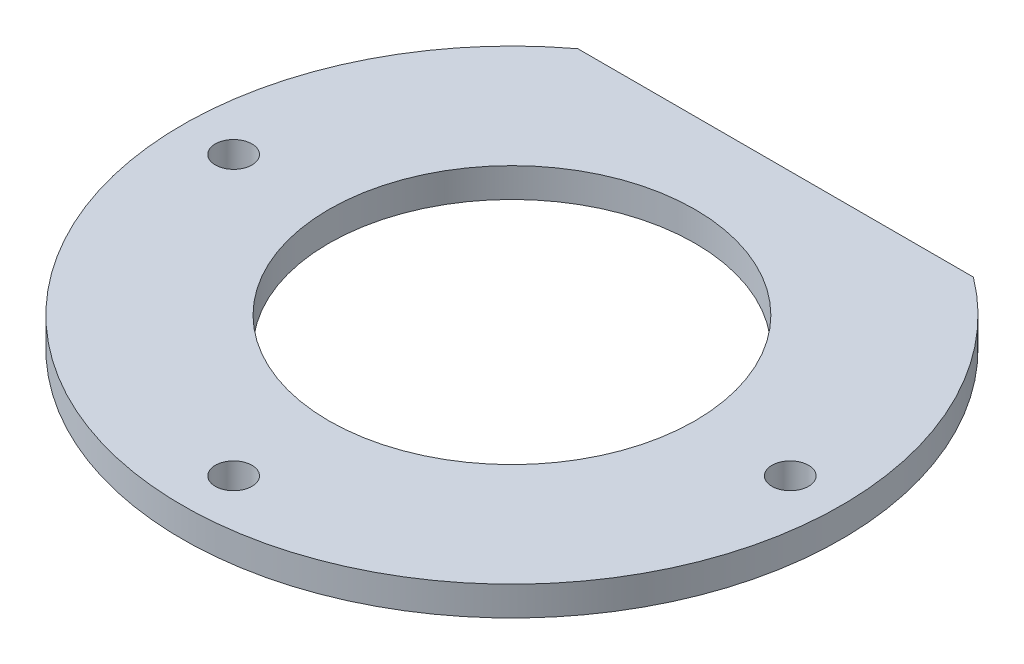
SolidWorks part; units mm, degrees
ref_plane "Спереди" through (0, 0, 0) normal (0, 0, 1) x (1, 0, 0)
ref_plane "Сверху" through (0, 0, 0) normal (0, 1, 0) x (1, 0, 0)
ref_plane "Справа" through (0, 0, 0) normal (1, 0, 0) x (0, 0, -1)
sketch "Эскиз1" plane through (0, 0, 0) normal (0, 1, 0) x (1, 0, 0)
  circle A0 centre (0, 0) radius 22.5
  circle A1 centre (0, 0) radius 12.5
  dimension "D1" = 45
  dimension "D2" = 25
extrude "Бобышка-Вытянуть1" add sketch "Эскиз1" along normal blind 2
sketch "Эскиз2" plane through (0, 2, 0) normal (0, 1, 0) x (1, 0, 0)
  line L0 (-20.2349, 18) -> (18.1213, 18)
  line L1 (0, 22.5) -> (0, -22.5) construction
  line L2 (-20.2349, 18) -> (0, 26.5423)
  line L3 (22.5, 0) -> (-22.5, 0) construction
  line L4 (0, 26.5423) -> (18.1213, 18)
  circle A0 centre (0, 0) radius 22.5 construction
  circle A1 centre (0, 0) radius 19 construction
  circle A2 centre (-19, 0) radius 1.25
  circle A3 centre (19, 0) radius 1.25
  circle A4 centre (0, -19) radius 1.25
  dimension "D1" = 38
  dimension "D2" = 2.5
  dimension "D3" = 2.5
  dimension "D4" = 2.5
  dimension "D5" = 18
extrude "Вырез-Вытянуть1" cut sketch "Эскиз2" against normal blind 2
